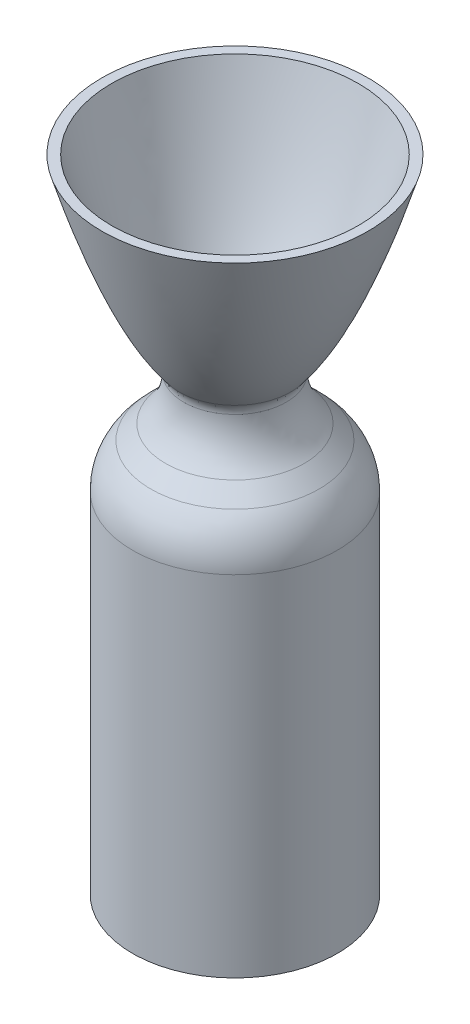
SolidWorks part; units mm, degrees
material "2018 Alloy"
ref_plane "Front Plane" through (0, 0, 0) normal (0, 0, 1) x (1, 0, 0)
ref_plane "Top Plane" through (0, 0, 0) normal (0, 1, 0) x (1, 0, 0)
ref_plane "Right Plane" through (0, 0, 0) normal (1, 0, 0) x (0, 0, -1)
sketch "Sketch1" plane through (0, 0, 0) normal (0, 0, 1) x (1, 0, 0)
  line L0 (-0.0055, 165.816) -> (-0.0055, -134.6871) construction
  line L1 (71.7275, 109.9275) -> (77.3884, 109.9275)
  line L4 (53.8815, -59.7275) -> (53.8815, -262.9275)
  line L7 (59.582, -59.7447) -> (59.582, -262.9447)
  line L8 (53.8815, -262.9275) -> (59.582, -262.9447)
  spline S0 degree 2 poles (26.7953, 6.5094) (49.2614, 34.6361) (71.7275, 109.9275) knots 0 0 0 1 1 1 construction
  spline S1 degree 2 poles (26.7953, 6.5094) (49.2614, 34.6361) (71.7275, 109.9275) knots 0 0 0 1 1 1
  spline S2 degree 4 poles (24.1269, -0.7179) (24.126, -0.7018) (24.1243, -0.6738) (24.121, -0.6546) (24.115, -0.5166) (24.1058, -0.4369) (24.0994, -0.1066) (24.0979, 0.0018) (24.102, 0.2678) (24.1085, 0.4272) (24.1205, 0.6469) (24.1414, 0.9016) (24.1752, 1.2027) (24.2265, 1.5422) (24.2905, 1.8812) (24.3671, 2.2165) (24.4563, 2.5494) (24.5577, 2.8783) (24.6716, 3.2035) (24.7972, 3.5238) (24.9353, 3.8398) (25.0841, 4.1494) (25.246, 4.4549) (25.4165, 4.7515) (25.6025, 5.0459) (25.7918, 5.3257) (26.0044, 5.6109) (26.1789, 5.8331) (26.3663, 6.0501) (26.5046, 6.2088) (26.757, 6.4728) (26.837, 6.5526) (27.1016, 6.806) (27.1881, 6.8783) (27.2854, 6.9667) (27.3038, 6.9803) (27.3264, 7.0004) knots 0 0 0 0 0 0.005192 0.010384 0.020768 0.041536 0.082569 0.102427 0.122284 0.142142 0.162 0.201716 0.241431 0.281147 0.320863 0.360578 0.400294 0.44001 0.479725 0.519441 0.559156 0.598872 0.638588 0.678303 0.718019 0.757735 0.79745 0.837166 0.857024 0.876882 0.916597 0.958047 0.979024 0.989512 1 1 1 1 1 construction
  spline S3 degree 4 poles (24.0991, 0.0002) (24.0991, 0.0361) (24.0996, 0.1103) (24.102, 0.2678) (24.1085, 0.4272) (24.1205, 0.6469) (24.1414, 0.9016) (24.1752, 1.2027) (24.2265, 1.5422) (24.2905, 1.8812) (24.3671, 2.2165) (24.4563, 2.5494) (24.5577, 2.8783) (24.6716, 3.2035) (24.7972, 3.5238) (24.9353, 3.8398) (25.0841, 4.1494) (25.246, 4.4549) (25.4165, 4.7515) (25.6025, 5.0459) (25.7918, 5.3257) (26.0044, 5.6109) (26.1789, 5.8331) (26.3663, 6.0501) (26.5046, 6.2088) (26.6704, 6.3823) (26.7445, 6.4586) (26.7953, 6.5094) knots 0.082569 0.082569 0.082569 0.082569 0.082569 0.102427 0.122284 0.142142 0.162 0.201716 0.241431 0.281147 0.320863 0.360578 0.400294 0.44001 0.479725 0.519441 0.559156 0.598872 0.638588 0.678303 0.718019 0.757735 0.79745 0.837166 0.857024 0.876882 0.916597 0.916597 0.916597 0.916597 0.916597
  spline S4 degree 4 poles (24.2082, 2.808) (24.2014, 2.7166) (24.1882, 2.5518) (24.1642, 2.1754) (24.1352, 1.6881) (24.1148, 1.1018) (24.103, 0.6556) (24.0988, 0.1104) (24.0988, -0.0999) (24.102, -0.543) (24.1083, -0.824) (24.1178, -1.1947) (24.1304, -1.5133) (24.1462, -1.8618) (24.1652, -2.1935) (24.1928, -2.6179) (24.2323, -3.1219) (24.3033, -3.8798) (24.4231, -4.8863) (24.5995, -6.0566) (24.8509, -7.385) (25.1518, -8.7034) (25.5018, -10.0095) (25.9004, -11.3017) (26.3469, -12.5779) (26.841, -13.8367) (27.3817, -15.076) (27.9685, -16.2944) (28.6001, -17.4898) (29.2765, -18.6611) (29.9954, -19.8056) (30.758, -20.9237) (31.4592, -21.8743) (32.0887, -22.6733) (32.6241, -23.3203) (33.0723, -23.8398) (33.5085, -24.3297) (33.9358, -24.7883) (34.2456, -25.1137) (34.6121, -25.4859) (34.7661, -25.6398) (35.1509, -26.0187) (35.4776, -26.3286) (35.905, -26.7273) (36.2395, -27.0242) (36.5192, -27.2707) (36.6465, -27.3798) (36.7148, -27.4387) (36.7496, -27.4686) knots 0 0 0 0 0 0.010393 0.020785 0.041571 0.062104 0.072371 0.082638 0.092575 0.102512 0.112449 0.122387 0.132324 0.142261 0.152198 0.162135 0.18201 0.201884 0.241633 0.281382 0.32113 0.360879 0.400628 0.440377 0.480126 0.519874 0.559623 0.599372 0.639121 0.67887 0.718618 0.758367 0.798116 0.81799 0.837865 0.857739 0.877613 0.897488 0.907425 0.917362 0.927629 0.937896 0.958429 0.979215 0.989607 0.994804 1 1 1 1 1 construction
  spline S5 degree 4 poles (24.0991, 0.0002) (24.0991, -0.0704) (24.0996, -0.2134) (24.102, -0.543) (24.1083, -0.824) (24.1178, -1.1947) (24.1304, -1.5133) (24.1462, -1.8618) (24.1652, -2.1935) (24.1928, -2.6179) (24.2323, -3.1219) (24.3033, -3.8798) (24.4231, -4.8863) (24.5995, -6.0566) (24.8509, -7.385) (25.1518, -8.7034) (25.5018, -10.0095) (25.9004, -11.3017) (26.3469, -12.5779) (26.841, -13.8367) (27.3817, -15.076) (27.9685, -16.2944) (28.6001, -17.4898) (29.2765, -18.6611) (29.9954, -19.8056) (30.758, -20.9237) (31.4592, -21.8743) (32.0887, -22.6733) (32.6241, -23.3203) (33.0723, -23.8398) (33.5085, -24.3297) (33.9358, -24.7883) (34.2456, -25.1137) (34.5369, -25.4095) (34.6364, -25.5098) (34.6863, -25.5597) knots 0.082638 0.082638 0.082638 0.082638 0.082638 0.092575 0.102512 0.112449 0.122387 0.132324 0.142261 0.152198 0.162135 0.18201 0.201884 0.241633 0.281382 0.32113 0.360879 0.400628 0.440377 0.480126 0.519874 0.559623 0.599372 0.639121 0.67887 0.718618 0.758367 0.798116 0.81799 0.837865 0.857739 0.877613 0.897488 0.907425 0.917362 0.917362 0.917362 0.917362 0.917362
  spline S6 degree 1 poles (34.6863, -25.5597) (43.2939, -34.1673) knots 0 0 1 1 construction
  spline S7 degree 1 poles (34.6863, -25.5597) (43.2939, -34.1673) knots 0 0 1 1
  spline S8 degree 4 poles (53.7724, -62.5352) (53.7792, -62.4464) (53.7924, -62.2737) (53.8104, -62.0016) (53.8309, -61.6599) (53.848, -61.2921) (53.8616, -60.9658) (53.8717, -60.5752) (53.8784, -60.2939) (53.8818, -59.8332) (53.8818, -59.6304) (53.8786, -59.1816) (53.8723, -58.9048) (53.8628, -58.5326) (53.8502, -58.2128) (53.8304, -57.7816) (53.8004, -57.281) (53.7562, -56.688) (53.6773, -55.8485) (53.5774, -55.0082) (53.4567, -54.1724) (53.2868, -53.1724) (53.0921, -52.1774) (52.8664, -51.1885) (52.61, -50.2075) (52.3293, -49.2331) (52.0243, -48.266) (51.6335, -47.1491) (51.1395, -45.8904) (50.5987, -44.651) (50.0121, -43.4327) (49.3801, -42.2371) (48.7041, -41.0662) (47.9845, -39.921) (47.2231, -38.8041) (46.5199, -37.8515) (45.8935, -37.0557) (45.3528, -36.4034) (44.9151, -35.8942) (44.5148, -35.447) (44.1815, -35.0846) (43.8739, -34.7603) (43.6741, -34.5515) (43.3653, -34.2383) (43.2159, -34.0889) (42.8277, -33.7066) (42.5041, -33.3998) (42.0741, -32.9986) (41.7412, -32.7033) (41.4607, -32.4559) (41.3338, -32.3472) (41.2653, -32.2883) (41.2305, -32.2583) knots 0 0 0 0 0 0.010393 0.020785 0.031178 0.041571 0.051838 0.062104 0.072371 0.082638 0.092575 0.102512 0.112449 0.122387 0.132324 0.142261 0.162135 0.18201 0.201884 0.241633 0.261507 0.281382 0.32113 0.360879 0.380754 0.400628 0.440377 0.480126 0.519874 0.559623 0.599372 0.639121 0.67887 0.718618 0.758367 0.798116 0.81799 0.837865 0.857739 0.877613 0.887551 0.897488 0.907425 0.917362 0.927629 0.937896 0.958429 0.979215 0.989607 0.994804 1 1 1 1 1 construction
  spline S9 degree 4 poles (53.8815, -59.7275) (53.8815, -59.657) (53.881, -59.5154) (53.8786, -59.1816) (53.8723, -58.9048) (53.8628, -58.5326) (53.8502, -58.2128) (53.8304, -57.7816) (53.8004, -57.281) (53.7562, -56.688) (53.6773, -55.8485) (53.5774, -55.0082) (53.4567, -54.1724) (53.2868, -53.1724) (53.0921, -52.1774) (52.8664, -51.1885) (52.61, -50.2075) (52.3293, -49.2331) (52.0243, -48.266) (51.6335, -47.1491) (51.1395, -45.8904) (50.5987, -44.651) (50.0121, -43.4327) (49.3801, -42.2371) (48.7041, -41.0662) (47.9845, -39.921) (47.2231, -38.8041) (46.5199, -37.8515) (45.8935, -37.0557) (45.3528, -36.4034) (44.9151, -35.8942) (44.5148, -35.447) (44.1815, -35.0846) (43.8739, -34.7603) (43.6741, -34.5515) (43.4444, -34.3185) (43.3438, -34.2172) (43.2939, -34.1673) knots 0.082638 0.082638 0.082638 0.082638 0.082638 0.092575 0.102512 0.112449 0.122387 0.132324 0.142261 0.162135 0.18201 0.201884 0.241633 0.261507 0.281382 0.32113 0.360879 0.380754 0.400628 0.440377 0.480126 0.519874 0.559623 0.599372 0.639121 0.67887 0.718618 0.758367 0.798116 0.81799 0.837865 0.857739 0.877613 0.887551 0.897488 0.907425 0.917362 0.917362 0.917362 0.917362 0.917362
  spline S10 degree 2 poles (32.4957, 6.4922) (54.9511, 34.6275) (77.3884, 109.9275) knots 0 0 0 1 1 1 construction
  spline S11 degree 2 poles (32.4957, 6.4922) (54.9511, 34.6275) (77.3884, 109.9275) knots 0 0 0 1 1 1
  spline S12 degree 4 poles (29.8273, -0.7351) (29.8264, -0.719) (29.8247, -0.691) (29.8214, -0.6718) (29.8155, -0.5338) (29.8063, -0.4541) (29.7998, -0.1238) (29.7984, -0.0154) (29.8025, 0.2506) (29.8089, 0.4101) (29.821, 0.6298) (29.8419, 0.8844) (29.8756, 1.1855) (29.9269, 1.525) (29.991, 1.864) (30.0676, 2.1993) (30.1568, 2.5322) (30.2582, 2.8611) (30.3721, 3.1863) (30.4976, 3.5066) (30.6357, 3.8227) (30.7845, 4.1323) (30.9464, 4.4378) (31.1169, 4.7343) (31.3029, 5.0287) (31.4922, 5.3085) (31.7048, 5.5937) (31.8793, 5.8159) (32.0668, 6.0329) (32.205, 6.1916) (32.4574, 6.4556) (32.5374, 6.5354) (32.802, 6.7888) (32.8885, 6.8611) (32.9858, 6.9496) (33.0042, 6.9632) (33.0268, 6.9832) knots 0 0 0 0 0 0.005192 0.010384 0.020768 0.041536 0.082569 0.102427 0.122284 0.142142 0.162 0.201716 0.241431 0.281147 0.320863 0.360578 0.400294 0.44001 0.479725 0.519441 0.559156 0.598872 0.638588 0.678303 0.718019 0.757735 0.79745 0.837166 0.857024 0.876882 0.916597 0.958047 0.979024 0.989512 1 1 1 1 1 construction
  spline S13 degree 4 poles (29.7995, -0.017) (29.7995, 0.0189) (29.8, 0.0931) (29.8025, 0.2506) (29.8089, 0.4101) (29.821, 0.6298) (29.8419, 0.8844) (29.8756, 1.1855) (29.9269, 1.525) (29.991, 1.864) (30.0676, 2.1993) (30.1568, 2.5322) (30.2582, 2.8611) (30.3721, 3.1863) (30.4976, 3.5066) (30.6357, 3.8227) (30.7845, 4.1323) (30.9464, 4.4378) (31.1169, 4.7343) (31.3029, 5.0287) (31.4922, 5.3085) (31.7048, 5.5937) (31.8793, 5.8159) (32.0668, 6.0329) (32.205, 6.1916) (32.3709, 6.3651) (32.445, 6.4415) (32.4957, 6.4922) knots 0.082569 0.082569 0.082569 0.082569 0.082569 0.102427 0.122284 0.142142 0.162 0.201716 0.241431 0.281147 0.320863 0.360578 0.400294 0.44001 0.479725 0.519441 0.559156 0.598872 0.638588 0.678303 0.718019 0.757735 0.79745 0.837166 0.857024 0.876882 0.916597 0.916597 0.916597 0.916597 0.916597
  spline S14 degree 4 poles (29.9087, 2.7908) (29.9018, 2.6994) (29.8886, 2.5346) (29.8646, 2.1582) (29.8357, 1.6709) (29.8153, 1.0846) (29.8034, 0.6384) (29.7992, 0.0932) (29.7992, -0.1171) (29.8024, -0.5602) (29.8087, -0.8412) (29.8182, -1.2118) (29.8309, -1.5304) (29.8467, -1.8789) (29.8656, -2.2107) (29.8933, -2.6351) (29.9327, -3.139) (30.0037, -3.897) (30.1236, -4.9035) (30.2999, -6.0737) (30.5513, -7.4022) (30.8522, -8.7206) (31.2022, -10.0266) (31.6008, -11.3188) (32.0474, -12.5951) (32.5414, -13.8539) (33.0821, -15.0932) (33.6689, -16.3116) (34.3006, -17.5069) (34.977, -18.6783) (35.6959, -19.8228) (36.4585, -20.9409) (37.1596, -21.8914) (37.7892, -22.6905) (38.3246, -23.3374) (38.7727, -23.857) (39.2089, -24.3468) (39.6363, -24.8055) (39.946, -25.1309) (40.3125, -25.5031) (40.4665, -25.657) (40.8513, -26.0359) (41.178, -26.3458) (41.6054, -26.7444) (41.94, -27.0414) (42.2196, -27.2879) (42.3469, -27.397) (42.4152, -27.4558) (42.45, -27.4857) knots 0 0 0 0 0 0.010393 0.020785 0.041571 0.062104 0.072371 0.082638 0.092575 0.102512 0.112449 0.122387 0.132324 0.142261 0.152198 0.162135 0.18201 0.201884 0.241633 0.281382 0.32113 0.360879 0.400628 0.440377 0.480126 0.519874 0.559623 0.599372 0.639121 0.67887 0.718618 0.758367 0.798116 0.81799 0.837865 0.857739 0.877613 0.897488 0.907425 0.917362 0.927629 0.937896 0.958429 0.979215 0.989607 0.994804 1 1 1 1 1 construction
  spline S15 degree 4 poles (29.7995, -0.017) (29.7995, -0.0875) (29.8, -0.2306) (29.8024, -0.5602) (29.8087, -0.8412) (29.8182, -1.2118) (29.8309, -1.5304) (29.8467, -1.8789) (29.8656, -2.2107) (29.8933, -2.6351) (29.9327, -3.139) (30.0037, -3.897) (30.1236, -4.9035) (30.2999, -6.0737) (30.5513, -7.4022) (30.8522, -8.7206) (31.2022, -10.0266) (31.6008, -11.3188) (32.0474, -12.5951) (32.5414, -13.8539) (33.0821, -15.0932) (33.6689, -16.3116) (34.3006, -17.5069) (34.977, -18.6783) (35.6959, -19.8228) (36.4585, -20.9409) (37.1596, -21.8914) (37.7892, -22.6905) (38.3246, -23.3374) (38.7727, -23.857) (39.2089, -24.3468) (39.6363, -24.8055) (39.946, -25.1309) (40.2373, -25.4267) (40.3368, -25.527) (40.3867, -25.5768) knots 0.082638 0.082638 0.082638 0.082638 0.082638 0.092575 0.102512 0.112449 0.122387 0.132324 0.142261 0.152198 0.162135 0.18201 0.201884 0.241633 0.281382 0.32113 0.360879 0.400628 0.440377 0.480126 0.519874 0.559623 0.599372 0.639121 0.67887 0.718618 0.758367 0.798116 0.81799 0.837865 0.857739 0.877613 0.897488 0.907425 0.917362 0.917362 0.917362 0.917362 0.917362
  spline S16 degree 1 poles (40.3867, -25.5768) (48.9943, -34.1845) knots 0 0 1 1 construction
  spline S17 degree 1 poles (40.3867, -25.5768) (48.9943, -34.1845) knots 0 0 1 1
  spline S18 degree 4 poles (59.4728, -62.5524) (59.4797, -62.4636) (59.4928, -62.2909) (59.5108, -62.0188) (59.5314, -61.6771) (59.5484, -61.3093) (59.562, -60.983) (59.5721, -60.5924) (59.5789, -60.3111) (59.5822, -59.8503) (59.5822, -59.6475) (59.5791, -59.1987) (59.5727, -58.922) (59.5632, -58.5497) (59.5506, -58.23) (59.5309, -57.7988) (59.5008, -57.2981) (59.4566, -56.7052) (59.3777, -55.8657) (59.2779, -55.0253) (59.1571, -54.1896) (58.9872, -53.1896) (58.7925, -52.1946) (58.5668, -51.2057) (58.3104, -50.2247) (58.0297, -49.2502) (57.7248, -48.2831) (57.334, -47.1663) (56.84, -45.9076) (56.2992, -44.6681) (55.7125, -43.4499) (55.0806, -42.2543) (54.4046, -41.0833) (53.6849, -39.9381) (52.9235, -38.8212) (52.2203, -37.8686) (51.594, -37.0728) (51.0533, -36.4206) (50.6156, -35.9114) (50.2152, -35.4642) (49.8819, -35.1018) (49.5744, -34.7775) (49.3745, -34.5687) (49.0657, -34.2554) (48.9163, -34.1061) (48.5281, -33.7238) (48.2045, -33.4169) (47.7745, -33.0158) (47.4416, -32.7205) (47.1611, -32.4731) (47.0342, -32.3644) (46.9658, -32.3055) (46.931, -32.2755) knots 0 0 0 0 0 0.010393 0.020785 0.031178 0.041571 0.051838 0.062104 0.072371 0.082638 0.092575 0.102512 0.112449 0.122387 0.132324 0.142261 0.162135 0.18201 0.201884 0.241633 0.261507 0.281382 0.32113 0.360879 0.380754 0.400628 0.440377 0.480126 0.519874 0.559623 0.599372 0.639121 0.67887 0.718618 0.758367 0.798116 0.81799 0.837865 0.857739 0.877613 0.887551 0.897488 0.907425 0.917362 0.927629 0.937896 0.958429 0.979215 0.989607 0.994804 1 1 1 1 1 construction
  spline S19 degree 4 poles (59.582, -59.7447) (59.582, -59.6742) (59.5814, -59.5326) (59.5791, -59.1987) (59.5727, -58.922) (59.5632, -58.5497) (59.5506, -58.23) (59.5309, -57.7988) (59.5008, -57.2981) (59.4566, -56.7052) (59.3777, -55.8657) (59.2779, -55.0253) (59.1571, -54.1896) (58.9872, -53.1896) (58.7925, -52.1946) (58.5668, -51.2057) (58.3104, -50.2247) (58.0297, -49.2502) (57.7248, -48.2831) (57.334, -47.1663) (56.84, -45.9076) (56.2992, -44.6681) (55.7125, -43.4499) (55.0806, -42.2543) (54.4046, -41.0833) (53.6849, -39.9381) (52.9235, -38.8212) (52.2203, -37.8686) (51.594, -37.0728) (51.0533, -36.4206) (50.6156, -35.9114) (50.2152, -35.4642) (49.8819, -35.1018) (49.5744, -34.7775) (49.3745, -34.5687) (49.1448, -34.3357) (49.0442, -34.2343) (48.9943, -34.1845) knots 0.082638 0.082638 0.082638 0.082638 0.082638 0.092575 0.102512 0.112449 0.122387 0.132324 0.142261 0.162135 0.18201 0.201884 0.241633 0.261507 0.281382 0.32113 0.360879 0.380754 0.400628 0.440377 0.480126 0.519874 0.559623 0.599372 0.639121 0.67887 0.718618 0.758367 0.798116 0.81799 0.837865 0.857739 0.877613 0.887551 0.897488 0.907425 0.917362 0.917362 0.917362 0.917362 0.917362
  dimension "D1" = 24.1046
  dimension "D2" = 53.8871
  dimension "D3" = 203.2
  dimension "D4" = 5.7004
  dimension "D7" = 24.0991
  dimension "D8" = 26.7953
  dimension "D9" = 34.6863
  dimension "D10" = 0.0002
revolve "Revolve2" add sketch "Sketch1" angle 360 about L0
